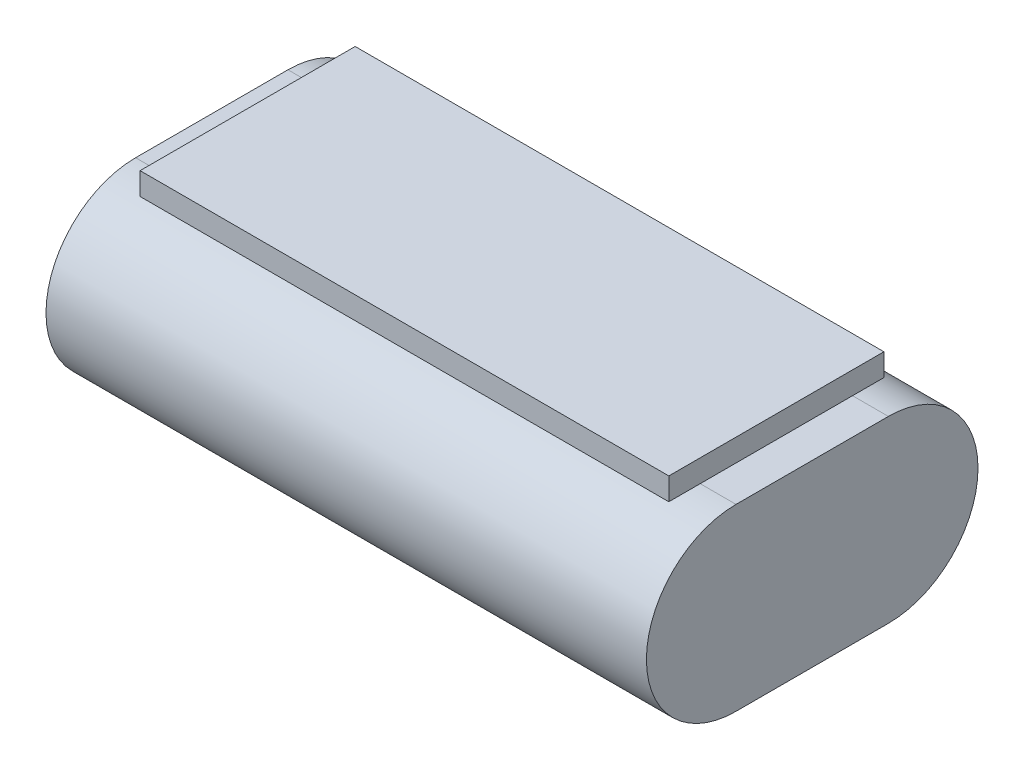
SolidWorks part; units mm, degrees
ref_plane "前视基准面" through (0, 0, 0) normal (0, 0, 1) x (1, 0, 0)
ref_plane "上视基准面" through (0, 0, 0) normal (0, 1, 0) x (1, 0, 0)
ref_plane "右视基准面" through (0, 0, 0) normal (1, 0, 0) x (0, 0, -1)
sketch "草图1" plane through (0, 0, 0) normal (1, 0, 0) x (0, 0, -1)
  line L0 (-8.5, 0) -> (8.5, 0) construction
  line L1 (-8.5, 10) -> (8.5, 10)
  line L2 (-8.5, -10) -> (8.5, -10)
  arc A0 (-8.5, 10) -> (-8.5, -10) centre (-8.5, 0) ccw
  arc A1 (8.5, -10) -> (8.5, 10) centre (8.5, 0) ccw
  point P3 (0, 0)
  point P8 (-18.5, 0)
  point P9 (18.5, 0)
  dimension "D1" = 20
  dimension "D2" = 37
extrude "凸台-拉伸1" add sketch "草图1" along normal mid plane 67
sketch "草图2" plane through (0, 10, 0) normal (0, 1, 0) x (1, 0, 0)
  line L1 (-29.5, -12) -> (29.5, -12)
  line L2 (-29.5, -12) -> (-29.5, 12)
  line L3 (-29.5, 12) -> (29.5, 12)
  line L4 (29.5, -12) -> (29.5, 12)
  line L5 (-29.5, -12) -> (29.5, 12) construction
  line L6 (-29.5, 12) -> (29.5, -12) construction
  point P0 (0, 0)
  dimension "D1" = 24
  dimension "D2" = 59
extrude "凸台-拉伸2" add sketch "草图2" along normal blind 2.5
